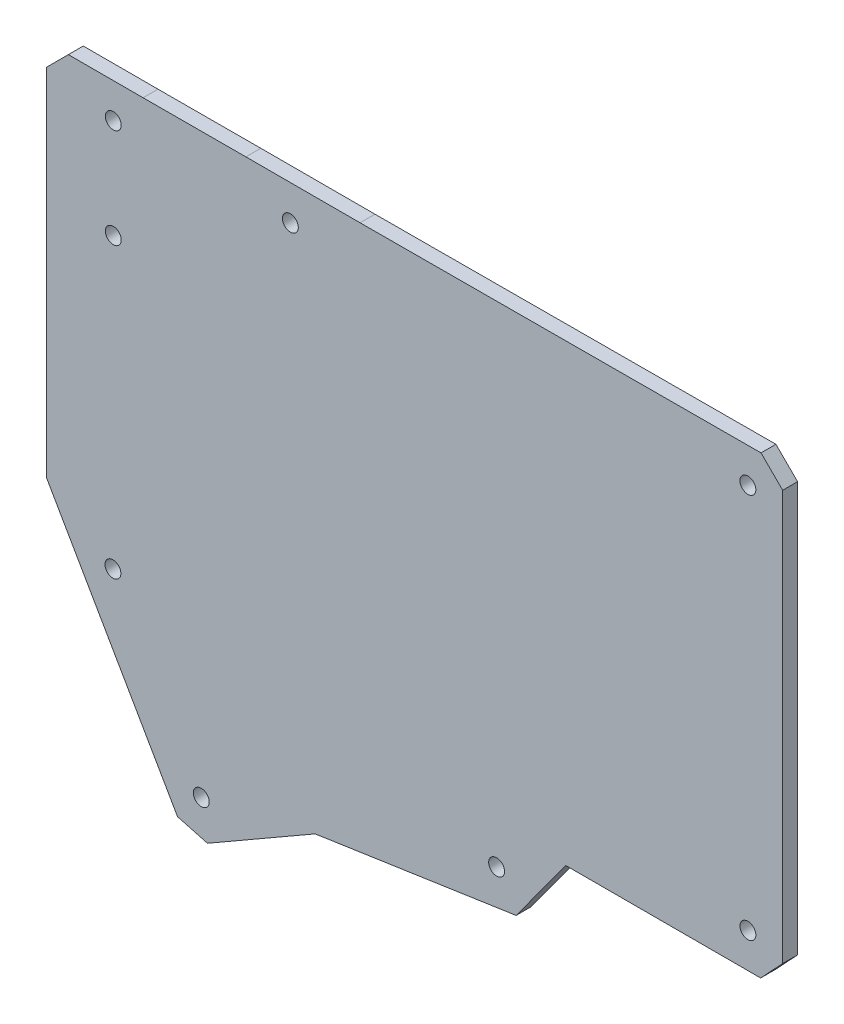
SolidWorks part; units mm, degrees
ref_plane "Plan de face" through (0, 0, 0) normal (0, 0, 1) x (1, 0, 0)
ref_plane "Plan de dessus" through (0, 0, 0) normal (0, 1, 0) x (1, 0, 0)
ref_plane "Plan de droite" through (0, 0, 0) normal (1, 0, 0) x (0, 0, -1)
sketch "Esquisse1" plane through (0, 0, 0) normal (0, 0, 1) x (1, 0, 0)
  line L0 (-117.3419, -15.4198) -> (-103.3409, -15.4198) construction
  line L1 (-103.3409, -15.4198) -> (-103.3409, -29.4208) construction
  line L2 (-103.3409, -29.4208) -> (-117.3419, -29.4208) construction
  line L3 (-117.3419, -29.4208) -> (-117.3419, -15.4198) construction
  line L4 (-98.3406, -27.0457) -> (-98.3406, -13.0447) construction
  line L5 (-98.3406, -13.0447) -> (-84.3396, -13.0447) construction
  line L6 (-84.3396, -13.0447) -> (-84.3396, -27.0457) construction
  line L7 (-84.3396, -27.0457) -> (-98.3406, -27.0457) construction
  line L8 (-79.3392, -24.6705) -> (-79.3392, -10.6695) construction
  line L9 (-79.3392, -10.6695) -> (-65.3382, -10.6695) construction
  line L10 (-65.3382, -10.6695) -> (-65.3382, -24.6705) construction
  line L11 (-65.3382, -24.6705) -> (-79.3392, -24.6705) construction
  line L12 (-60.3379, -27.0457) -> (-60.3379, -13.0447) construction
  line L13 (-60.3379, -13.0447) -> (-46.3369, -13.0447) construction
  line L14 (-46.3369, -13.0447) -> (-46.3369, -27.0457) construction
  line L15 (-46.3369, -27.0457) -> (-60.3379, -27.0457) construction
  line L16 (-41.3365, -31.796) -> (-41.3365, -17.795) construction
  line L17 (-41.3365, -17.795) -> (-27.3355, -17.795) construction
  line L18 (-27.3355, -17.795) -> (-27.3355, -31.796) construction
  line L19 (-27.3355, -31.796) -> (-41.3365, -31.796) construction
  line L20 (-22.3347, -31.796) -> (-22.3347, -17.795) construction
  line L21 (-22.3347, -17.795) -> (-8.3337, -17.795) construction
  line L22 (-8.3337, -17.795) -> (-8.3337, -31.796)
  line L23 (-8.3337, -31.796) -> (-22.3347, -31.796) construction
  line L24 (-117.3419, -34.4212) -> (-103.3409, -34.4212) construction
  line L25 (-103.3409, -34.4212) -> (-103.3409, -48.4222) construction
  line L26 (-103.3409, -48.4222) -> (-117.3419, -48.4222) construction
  line L27 (-117.3419, -48.4222) -> (-117.3419, -34.4212) construction
  line L28 (-98.3406, -32.046) -> (-84.3396, -32.046) construction
  line L29 (-84.3396, -32.046) -> (-84.3396, -46.047) construction
  line L30 (-84.3396, -46.047) -> (-98.3406, -46.047) construction
  line L31 (-98.3406, -46.047) -> (-98.3406, -32.046) construction
  line L32 (-79.3392, -29.6709) -> (-65.3382, -29.6709) construction
  line L33 (-65.3382, -29.6709) -> (-65.3382, -43.6718) construction
  line L34 (-65.3382, -43.6718) -> (-79.3392, -43.6718) construction
  line L35 (-79.3392, -43.6718) -> (-79.3392, -29.6709) construction
  line L36 (-60.3379, -32.046) -> (-46.3369, -32.046) construction
  line L37 (-46.3369, -32.046) -> (-46.3369, -46.047) construction
  line L38 (-46.3369, -46.047) -> (-60.3379, -46.047) construction
  line L39 (-60.3379, -46.047) -> (-60.3379, -32.046) construction
  line L40 (-41.3365, -36.7964) -> (-27.3355, -36.7964) construction
  line L41 (-27.3355, -36.7964) -> (-27.3355, -50.7973) construction
  line L42 (-27.3355, -50.7973) -> (-41.3365, -50.7973) construction
  line L43 (-41.3365, -50.7973) -> (-41.3365, -36.7964) construction
  line L44 (-22.3347, -36.7964) -> (-8.3337, -36.7964) construction
  line L45 (-8.3337, -36.7964) -> (-8.3337, -50.7973) construction
  line L46 (-8.3337, -50.7973) -> (-22.3347, -50.7973) construction
  line L47 (-22.3347, -50.7973) -> (-22.3347, -36.7964) construction
  line L48 (-22.3347, -55.7977) -> (-8.3337, -55.7977) construction
  line L49 (-8.3337, -55.7977) -> (-8.3337, -69.7987) construction
  line L50 (-8.3337, -69.7987) -> (-22.3347, -69.7987) construction
  line L51 (-22.3347, -69.7987) -> (-22.3347, -55.7977) construction
  line L52 (-41.3365, -55.7977) -> (-27.3355, -55.7977) construction
  line L53 (-27.3355, -55.7977) -> (-27.3355, -69.7987) construction
  line L54 (-27.3355, -69.7987) -> (-41.3365, -69.7987) construction
  line L55 (-41.3365, -69.7987) -> (-41.3365, -55.7977) construction
  line L56 (-60.3379, -51.0474) -> (-46.3369, -51.0474) construction
  line L57 (-46.3369, -51.0474) -> (-46.3369, -65.0484) construction
  line L58 (-46.3369, -65.0484) -> (-60.3379, -65.0484) construction
  line L59 (-60.3379, -65.0484) -> (-60.3379, -51.0474) construction
  line L60 (-79.3392, -48.6722) -> (-65.3382, -48.6722) construction
  line L61 (-65.3382, -48.6722) -> (-65.3382, -62.6732) construction
  line L62 (-65.3382, -62.6732) -> (-79.3392, -62.6732) construction
  line L63 (-79.3392, -62.6732) -> (-79.3392, -48.6722) construction
  line L64 (-98.3406, -51.0474) -> (-84.3396, -51.0474) construction
  line L65 (-84.3396, -51.0474) -> (-84.3396, -65.0484) construction
  line L66 (-84.3396, -65.0484) -> (-98.3406, -65.0484) construction
  line L67 (-98.3406, -65.0484) -> (-98.3406, -51.0474) construction
  line L68 (-117.3419, -53.4225) -> (-103.3409, -53.4225) construction
  line L69 (-103.3409, -53.4225) -> (-103.3409, -67.4235) construction
  line L70 (-103.3409, -67.4235) -> (-117.3419, -67.4235) construction
  line L71 (-117.3419, -67.4235) -> (-117.3419, -53.4225) construction
  line L72 (-88.8399, -70.6738) -> (-74.8389, -70.6738) construction
  line L73 (-74.8389, -70.6738) -> (-74.8389, -84.6747) construction
  line L74 (-74.8389, -84.6747) -> (-88.8399, -84.6747) construction
  line L75 (-88.8399, -84.6747) -> (-88.8399, -70.6738) construction
  line L76 (-111.4175, -75.4665) -> (-97.8899, -71.8565) construction
  line L77 (-97.8899, -71.8565) -> (-94.28, -85.3841) construction
  line L78 (-94.28, -85.3841) -> (-107.8075, -88.9941) construction
  line L79 (-107.8075, -88.9941) -> (-111.4175, -75.4665) construction
  line L80 (-134.6581, -81.5997) -> (-122.5281, -74.6075) construction
  line L81 (-122.5281, -74.6075) -> (-115.5359, -86.7375) construction
  line L82 (-115.5359, -86.7375) -> (-127.6659, -93.7297) construction
  line L83 (-127.6659, -93.7297) -> (-134.6581, -81.5997) construction
  line L86 (-25.3391, -71.9336) -> (-62.0853, -71.9336) construction
  line L89 (-72.824, -86.6446) -> (-62.0853, -71.9336) construction
  line L96 (-109.7697, -91.4639) -> (-73.0906, -86.6918) construction
  line L97 (-124.664, -99.8297) -> (-110.3971, -91.5881) construction
  line L98 (-139.9408, -76.5013) -> (-126.7151, -99.4281) construction
  line L99 (-119.8527, -15.5421) -> (-139.6028, -15.5421) construction
  line L100 (-100.8528, -13.2921) -> (-118.8527, -13.2921) construction
  line L101 (-63.8455, -8.5421) -> (-80.8528, -8.5421) construction
  line L102 (-44.8455, -10.792) -> (-62.8485, -10.792) construction
  line L103 (-25.8456, -15.5421) -> (-43.8486, -15.5421) construction
  line L104 (-6.8456, -15.5421) -> (-23.8529, -15.5421) construction
  line L105 (-6.2741, -71.3672) -> (-6.2741, -16.1136) construction
  line L106 (-23.8529, -71.9423) -> (-6.8456, -71.9423) construction
  line L107 (-61.8455, -71.9423) -> (-25.8456, -71.9423) construction
  line L108 (-72.6738, -86.4911) -> (-62.1363, -72.0583) construction
  line L109 (-140.1743, -16.1136) -> (-140.1743, -75.5958) construction
  line L110 (-134.3462, 1.5705) -> (-134.3466, -55.7217) construction
  line L111 (-134.3466, -55.7217) -> (-160.479, -70.8411) construction
  line L112 (-160.479, -70.8411) -> (-133.7613, -117.344) construction
  line L113 (-126.937, -119.1852) -> (-105.0783, -106.604) construction
  line L114 (-105.0783, -106.604) -> (-64.4097, -100.5586) construction
  line L115 (-64.4097, -100.5586) -> (-54.4636, -86.9336) construction
  line L116 (3.6609, -86.9336) -> (-54.4636, -86.9336) construction
  line L117 (-10.3389, -81.6486) -> (-10.3389, 1.6248) construction
  line L122 (3.6609, 6.6672) -> (-96.3687, 6.3642) construction
  line L129 (-10.3391, -86.9336) -> (-10.3391, -0.337) construction
  line L130 (-48.3676, 6.5096) -> (-96.3687, 6.3642) construction
  line L131 (-115.3458, 1.5705) -> (-134.3462, 1.5705) construction
  line L132 (-160.479, -3.4295) -> (-160.479, -70.8411) construction
  line L134 (-119.3456, 1.5429) -> (-119.3464, -12.4295) construction
  line L136 (-140.0228, -78.3428) -> (-140.0228, 1.5705) construction
  line L138 (-160.479, -70.8411) -> (-131.2704, -121.6794) construction
  line L139 (-131.2704, -121.6794) -> (-105.0783, -106.604) construction
  line L140 (-133.7613, -117.344) -> (-126.937, -119.1852) construction
  line L142 (-10.3389, 1.6248) -> (-15.3389, 6.6096) construction
  line L143 (-10.3391, -86.9336) -> (-54.4636, -86.9336) construction
  line L144 (-10.3389, -81.6486) -> (-15.3389, -86.9912) construction
  line L147 (-103.3652, 6.3642) -> (-96.3687, 6.3642) construction
  line L148 (-103.3652, 6.3642) -> (-119.3456, 6.3642) construction
  line L149 (-119.3456, 6.3642) -> (-119.3456, 1.5429) construction
  line L150 (-140.0228, 1.5705) -> (-140.0228, 6.3209) construction
  line L151 (-140.0228, 6.3209) -> (-155.479, 6.3209) construction
  line L152 (-160.479, 1.3209) -> (-160.479, -3.4295) construction
  line L153 (-155.479, 6.3209) -> (-160.479, 1.3209) construction
  line L154 (8.6609, -1.3177) -> (-119.3458, -1.7055) construction
  line L155 (-146.0924, -79.8227) -> (-128.3223, -110.752) construction
  line L156 (-128.3223, -110.752) -> (-107.7547, -98.9139) construction
  line L157 (-140.0228, -78.3428) -> (-126.1111, -102.5565) construction
  line L158 (-126.1111, -102.5565) -> (-109.762, -93.1464) construction
  line L159 (-109.762, -93.1464) -> (-72.2631, -87.5722) construction
  line L160 (-72.2631, -87.5722) -> (-61.5772, -72.9336) construction
  line L161 (-24.3391, -72.9336) -> (-61.5772, -72.9336) construction
  line L162 (-24.3391, -72.9336) -> (-24.3391, -14.337) construction
  line L163 (-24.3391, -14.337) -> (-43.3418, -14.337) construction
  line L164 (-43.3418, -14.337) -> (-43.3418, -9.7225) construction
  line L165 (-43.3418, -9.7225) -> (-62.3174, -9.781) construction
  line L166 (-62.3174, -9.781) -> (-62.3244, -7.5328) construction
  line L167 (-62.3244, -7.5328) -> (-82.3255, -7.5934) construction
  line L168 (-82.3255, -7.5934) -> (-82.3183, -9.9293) construction
  line L169 (-82.3183, -9.9293) -> (-101.3458, -9.9293) construction
  line L170 (-101.3458, -9.9293) -> (-101.3458, -12.4295) construction
  line L171 (-101.3458, -12.4295) -> (-119.3464, -12.4295) construction
  line L172 (-120.3463, -12.4295) -> (-120.3466, -63.7961) construction
  line L173 (-120.3466, -63.7961) -> (-140.5236, -75.4699) construction
  line L174 (-107.7547, -98.9139) -> (-68.8973, -93.1378) construction
  line L175 (-68.8973, -93.1378) -> (-58.5285, -78.9336) construction
  line L176 (-18.3391, -78.9336) -> (-58.5285, -78.9336) construction
  line L177 (-18.3391, -78.9336) -> (-18.3391, -1.3419) construction
  line L178 (-62.3425, -1.5328) -> (-82.3437, -1.5934) construction
  line L179 (-18.3391, -78.9336) -> (-18.3391, -14.337) construction
  line L180 (-146.0228, -76.3355) -> (-146.0228, 1.5705) construction
  line L181 (-140.0228, -76.3355) -> (-140.0228, 1.5705) construction
  line L183 (-140.0228, 6.3209) -> (-119.3456, 6.3642) construction
  line L184 (-120.3463, -12.4295) -> (-120.3466, -64.3728) construction
  line L185 (-119.8474, -63.5072) -> (-140.5236, -75.4699) construction
  line L186 (-101.3458, -12.4295) -> (-120.3463, -12.4295) construction
  line L187 (-140.8899, -76.8336) -> (-126.1111, -102.5565) construction
  line L188 (-146.0228, -4.8879) -> (-143.2428, -3.2829) construction
  line L189 (-143.2428, -3.2829) -> (-143.2428, -0.0728) construction
  line L190 (-143.2428, -0.0728) -> (-146.0228, 1.5322) construction
  line L191 (-146.0228, 1.5322) -> (-148.8028, -0.0728) construction
  line L192 (-148.8028, -0.0728) -> (-148.8028, -3.2829) construction
  line L193 (-148.8028, -3.2829) -> (-146.0228, -4.8879) construction
  line L194 (-110.3971, -4.8884) -> (-107.6171, -3.2834) construction
  line L195 (-107.6171, -3.2834) -> (-107.6171, -0.0733) construction
  line L196 (-107.6171, -0.0733) -> (-110.3971, 1.5317) construction
  line L197 (-110.3971, 1.5317) -> (-113.1771, -0.0733) construction
  line L198 (-113.1771, -0.0733) -> (-113.1771, -3.2834) construction
  line L199 (-113.1771, -3.2834) -> (-110.3971, -4.8884) construction
  line L200 (-18.3391, -4.552) -> (-15.5591, -2.947) construction
  line L201 (-15.5591, -2.947) -> (-15.5591, 0.2631) construction
  line L202 (-15.5591, 0.2631) -> (-18.3391, 1.8681) construction
  line L203 (-18.3391, 1.8681) -> (-21.1191, 0.2631) construction
  line L204 (-21.1191, 0.2631) -> (-21.1191, -2.947) construction
  line L205 (-21.1191, -2.947) -> (-18.3391, -4.552) construction
  line L206 (-18.3391, -75.7236) -> (-21.1191, -77.3286) construction
  line L207 (-21.1191, -77.3286) -> (-21.1191, -80.5387) construction
  line L208 (-21.1191, -80.5387) -> (-18.3391, -82.1437) construction
  line L209 (-18.3391, -82.1437) -> (-15.5591, -80.5387) construction
  line L210 (-15.5591, -80.5387) -> (-15.5591, -77.3286) construction
  line L211 (-15.5591, -77.3286) -> (-18.3391, -75.7236) construction
  line L212 (-70.6661, -90.459) -> (-72.1016, -93.3302) construction
  line L213 (-72.1016, -93.3302) -> (-70.3329, -96.009) construction
  line L217 (-25.3391, -71.9336) -> (-25.3391, -15.337) construction
  line L220 (-25.3391, -15.337) -> (-44.3418, -15.337) construction
  line L221 (-44.3418, -15.337) -> (-44.3418, -10.7256) construction
  line L222 (-44.3418, -10.7256) -> (-63.3143, -10.7841) construction
  line L223 (-63.3143, -10.7841) -> (-63.3213, -8.5358) construction
  line L224 (-63.3213, -8.5358) -> (-81.3225, -8.5903) construction
  line L225 (-81.3225, -8.5903) -> (-81.3152, -10.9293) construction
  line L226 (-81.3152, -10.9293) -> (-100.3458, -10.9293) construction
  line L227 (-100.3458, -10.9293) -> (-100.3458, -13.4295) construction
  line L228 (-100.3458, -13.4295) -> (-119.3463, -13.4295) construction
  line L231 (-119.3463, -13.4295) -> (-119.3466, -64.3728) construction
  line L232 (-119.3466, -64.3728) -> (-140.0228, -76.3355) construction
  line L233 (-140.0228, -76.3355) -> (-125.7426, -101.1906) construction
  line L234 (-125.7426, -101.1906) -> (-110.0965, -92.1851) construction
  line L235 (-110.0965, -92.1851) -> (-72.824, -86.6446) construction
  line L236 (-70.3329, -96.009) -> (-67.1286, -95.8166) construction
  line L237 (-67.1286, -95.8166) -> (-65.693, -92.9454) construction
  line L238 (-65.693, -92.9454) -> (-67.4618, -90.2666) construction
  line L239 (-67.4618, -90.2666) -> (-70.6661, -90.459) construction
  line L240 (-129.9214, -107.9687) -> (-131.5323, -110.7453) construction
  line L241 (-131.5323, -110.7453) -> (-129.9331, -113.5286) construction
  line L242 (-129.9331, -113.5286) -> (-126.7231, -113.5354) construction
  line L243 (-126.7231, -113.5354) -> (-125.1122, -110.7588) construction
  line L244 (-125.1122, -110.7588) -> (-126.7114, -107.9754) construction
  line L245 (-126.7114, -107.9754) -> (-129.9214, -107.9687) construction
  line L246 (-144.4932, -82.606) -> (-142.8823, -79.8294) construction
  line L247 (-142.8823, -79.8294) -> (-144.4815, -77.0461) construction
  line L248 (-144.4815, -77.0461) -> (-147.6915, -77.0393) construction
  line L249 (-147.6915, -77.0393) -> (-149.3024, -79.8159) construction
  line L250 (-149.3024, -79.8159) -> (-147.7033, -82.5993) construction
  line L251 (-147.7033, -82.5993) -> (-144.4932, -82.606) construction
  line L252 (-15.6936, 5.6086) -> (-96.3671, 5.3642)
  line L253 (-103.3652, 5.3642) -> (-96.3671, 5.3642)
  line L254 (-103.3652, 5.3642) -> (-119.3446, 5.3642)
  line L255 (-140.0218, 5.3209) -> (-119.3446, 5.3642)
  line L256 (-140.0218, 5.3209) -> (-155.0648, 5.3209)
  line L257 (-155.0648, 5.3209) -> (-159.479, 0.9066)
  line L258 (-159.479, 0.9066) -> (-159.479, -3.4295)
  line L259 (-159.479, -3.4295) -> (-159.479, -70.5743)
  line L260 (-159.479, -70.5743) -> (-133.1007, -116.4865)
  line L261 (-133.1007, -116.4865) -> (-127.0766, -118.1118)
  line L262 (-127.0766, -118.1118) -> (-105.4129, -105.6427)
  line L263 (-105.4129, -105.6427) -> (-64.9706, -99.631)
  line L264 (-64.9706, -99.631) -> (-54.9717, -85.9336)
  line L265 (-15.7729, -85.9336) -> (-54.9717, -85.9336)
  line L266 (-11.3391, -81.1961) -> (-15.7729, -85.9336)
  line L267 (-11.3391, -81.1961) -> (-11.3391, 1.2672)
  line L268 (-11.3391, 1.2672) -> (-15.6936, 5.6086)
  line L269 (8.6609, -81.591) -> (3.6609, -86.9336) construction
  line L270 (7.6609, -81.1961) -> (3.2271, -85.9336) construction
  line L271 (8.6609, -81.591) -> (8.6609, 1.6823) construction
  line L272 (7.6609, -81.1961) -> (7.6609, 1.2672) construction
  line L273 (8.6609, 1.6823) -> (3.6609, 6.6672) construction
  line L274 (7.6609, 1.2672) -> (3.2488, 5.6659) construction
  line L276 (3.2488, 5.6659) -> (-96.3671, 5.3642) construction
  line L277 (3.2271, -85.9336) -> (-54.9717, -85.9336) construction
  line L328 (-48.3607, 4.2621) -> (-48.3676, 6.5096) construction
  line L329 (-29.3418, 4.3208) -> (-48.3607, 4.2621) construction
  line L330 (-29.3418, -0.337) -> (-29.3418, 4.3208) construction
  line L331 (-10.3391, -0.337) -> (-29.3418, -0.337) construction
  line L332 (-115.3458, 4.0707) -> (-115.3458, 1.5705) construction
  line L333 (-96.3616, 4.0707) -> (-115.3458, 4.0707) construction
  line L334 (-96.3687, 6.3642) -> (-96.3616, 4.0707) construction
  circle A2 centre (-18.3391, -1.3419) radius 1.6
  circle A3 centre (-18.3391, -1.3419) radius 3 construction
  circle A4 centre (-110.3971, -1.6784) radius 1.6
  circle A5 centre (-18.3391, -78.9336) radius 1.6
  circle A6 centre (-68.8973, -93.1378) radius 1.6
  circle A7 centre (-128.3223, -110.752) radius 1.6
  circle A8 centre (-146.0924, -79.8227) radius 1.6
  circle A9 centre (-146.0228, -1.6779) radius 1.6
  circle A10 centre (-146.0228, -1.6779) radius 2.78 construction
  circle A11 centre (-110.3971, -1.6784) radius 2.78 construction
  circle A12 centre (-18.3391, -1.3419) radius 2.78 construction
  circle A13 centre (-18.3391, -78.9336) radius 2.78 construction
  circle A14 centre (-68.8973, -93.1378) radius 2.78 construction
  circle A15 centre (-128.3223, -110.752) radius 2.78 construction
  circle A16 centre (-146.0924, -79.8227) radius 2.78 construction
  circle A17 centre (-146.0228, -21.6779) radius 1.6
  point P138 (-160.479, 1.5705)
  point P139 (-10.3389, 6.6248)
  point P150 (-160.479, 6.3209)
  point P197 (-15.5591, -1.3419)
  dimension "D3" = 3.2
  dimension "D4" = 6
  dimension "D6" = 3.2
  dimension "D7" = 3.2
  dimension "D8" = 3.2
  dimension "D9" = 3.2
  dimension "D10" = 3.2
  dimension "D15" = 3.2
  dimension "D24" = 3.2
  dimension "D2" = 6
  dimension "D1" = 15
  dimension "D16" = 5.56
  dimension "D17" = 5.56
  dimension "D18" = 5.56
  dimension "D19" = 5.56
  dimension "D20" = 5.56
  dimension "D21" = 5.56
  dimension "D22" = 5.56
  dimension "D25" = 20
  dimension "D5" = 1
  dimension "D13" = 6
  dimension "D23" = 1
extrude "Boss.-Extru.1" add sketch "Esquisse1" along normal blind 3
